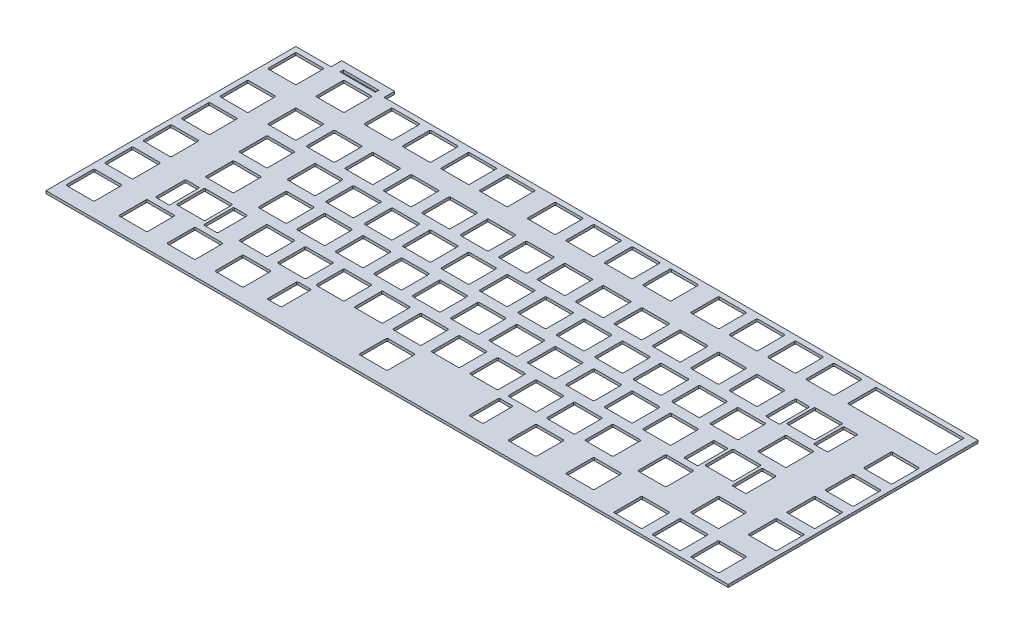
SolidWorks part; units mm, degrees
ref_plane "Front" through (0, 0, 0) normal (0, 0, 1) x (1, 0, 0)
ref_plane "Top" through (0, 0, 0) normal (0, 1, 0) x (1, 0, 0)
ref_plane "Right" through (0, 0, 0) normal (1, 0, 0) x (0, 0, -1)
sketch "Sketch5" plane through (0, 0, 0) normal (0, 1, 0) x (1, 0, 0)
  line L0 (3.4571, -2.8857) -> (18.3143, -2.8857)
  line L1 (3.4571, -18.8857) -> (18.3143, -18.8857)
  line L2 (2.8857, -3.4571) -> (2.8857, -18.3143)
  line L3 (18.8857, -3.4571) -> (18.8857, -18.3143)
  line L4 (30.6714, -2.8857) -> (45.5286, -2.8857)
  line L5 (30.6714, -18.8857) -> (45.5286, -18.8857)
  line L6 (30.1, -3.4571) -> (30.1, -18.3143)
  line L7 (46.1, -3.4571) -> (46.1, -18.3143)
  line L8 (57.8857, -2.8857) -> (72.7429, -2.8857)
  line L9 (57.8857, -18.8857) -> (72.7429, -18.8857)
  line L10 (57.3143, -3.4571) -> (57.3143, -18.3143)
  line L11 (73.3143, -3.4571) -> (73.3143, -18.3143)
  line L12 (79.6571, -2.8857) -> (94.5143, -2.8857)
  line L13 (79.6571, -18.8857) -> (94.5143, -18.8857)
  line L14 (79.0857, -3.4571) -> (79.0857, -18.3143)
  line L15 (95.0857, -3.4571) -> (95.0857, -18.3143)
  line L16 (101.4286, -2.8857) -> (116.2857, -2.8857)
  line L17 (101.4286, -18.8857) -> (116.2857, -18.8857)
  line L18 (100.8571, -3.4571) -> (100.8571, -18.3143)
  line L19 (116.8571, -3.4571) -> (116.8571, -18.3143)
  line L20 (123.2, -2.8857) -> (138.0571, -2.8857)
  line L21 (123.2, -18.8857) -> (138.0571, -18.8857)
  line L22 (122.6286, -3.4571) -> (122.6286, -18.3143)
  line L23 (138.6286, -3.4571) -> (138.6286, -18.3143)
  line L24 (150.4143, -2.8857) -> (165.2714, -2.8857)
  line L25 (150.4143, -18.8857) -> (165.2714, -18.8857)
  line L26 (149.8429, -3.4571) -> (149.8429, -18.3143)
  line L27 (165.8429, -3.4571) -> (165.8429, -18.3143)
  line L28 (172.1857, -2.8857) -> (187.0429, -2.8857)
  line L29 (172.1857, -18.8857) -> (187.0429, -18.8857)
  line L30 (171.6143, -3.4571) -> (171.6143, -18.3143)
  line L31 (187.6143, -3.4571) -> (187.6143, -18.3143)
  line L32 (193.9571, -2.8857) -> (208.8143, -2.8857)
  line L33 (193.9571, -18.8857) -> (208.8143, -18.8857)
  line L34 (193.3857, -3.4571) -> (193.3857, -18.3143)
  line L35 (209.3857, -3.4571) -> (209.3857, -18.3143)
  line L36 (215.7286, -2.8857) -> (230.5857, -2.8857)
  line L37 (215.7286, -18.8857) -> (230.5857, -18.8857)
  line L38 (215.1571, -3.4571) -> (215.1571, -18.3143)
  line L39 (231.1571, -3.4571) -> (231.1571, -18.3143)
  line L40 (242.9429, -2.8857) -> (257.8, -2.8857)
  line L41 (242.9429, -18.8857) -> (257.8, -18.8857)
  line L42 (242.3714, -3.4571) -> (242.3714, -18.3143)
  line L43 (258.3714, -3.4571) -> (258.3714, -18.3143)
  line L44 (264.7143, -2.8857) -> (279.5714, -2.8857)
  line L45 (264.7143, -18.8857) -> (279.5714, -18.8857)
  line L46 (264.1429, -3.4571) -> (264.1429, -18.3143)
  line L47 (280.1429, -3.4571) -> (280.1429, -18.3143)
  line L48 (286.4857, -2.8857) -> (301.3429, -2.8857)
  line L49 (286.4857, -18.8857) -> (301.3429, -18.8857)
  line L50 (285.9143, -3.4571) -> (285.9143, -18.3143)
  line L51 (301.9143, -3.4571) -> (301.9143, -18.3143)
  line L52 (308.2571, -2.8857) -> (323.1143, -2.8857)
  line L53 (308.2571, -18.8857) -> (323.1143, -18.8857)
  line L54 (307.6857, -3.4571) -> (307.6857, -18.3143)
  line L55 (323.6857, -3.4571) -> (323.6857, -18.3143)
  line L57 (331.4831, -2.8857) -> (381.4831, -2.8857)
  line L58 (331.4831, -2.8857) -> (331.4831, -18.8857)
  line L59 (331.4831, -18.8857) -> (381.4831, -18.8857)
  line L60 (381.4831, -2.8857) -> (381.4831, -18.8857)
  line L68 (3.4571, -30.1) -> (18.3143, -30.1)
  line L69 (3.4571, -46.1) -> (18.3143, -46.1)
  line L70 (2.8857, -30.6714) -> (2.8857, -45.5286)
  line L71 (18.8857, -30.6714) -> (18.8857, -45.5286)
  line L72 (30.6714, -30.1) -> (45.5286, -30.1)
  line L73 (30.6714, -46.1) -> (45.5286, -46.1)
  line L74 (30.1, -30.6714) -> (30.1, -45.5286)
  line L75 (46.1, -30.6714) -> (46.1, -45.5286)
  line L76 (52.4429, -30.1) -> (67.3, -30.1)
  line L77 (52.4429, -46.1) -> (67.3, -46.1)
  line L78 (51.8714, -30.6714) -> (51.8714, -45.5286)
  line L79 (67.8714, -30.6714) -> (67.8714, -45.5286)
  line L80 (74.2143, -30.1) -> (89.0714, -30.1)
  line L81 (74.2143, -46.1) -> (89.0714, -46.1)
  line L82 (73.6429, -30.6714) -> (73.6429, -45.5286)
  line L83 (89.6429, -30.6714) -> (89.6429, -45.5286)
  line L84 (95.9857, -30.1) -> (110.8429, -30.1)
  line L85 (95.9857, -46.1) -> (110.8429, -46.1)
  line L86 (95.4143, -30.6714) -> (95.4143, -45.5286)
  line L87 (111.4143, -30.6714) -> (111.4143, -45.5286)
  line L88 (117.7571, -30.1) -> (132.6143, -30.1)
  line L89 (117.7571, -46.1) -> (132.6143, -46.1)
  line L90 (117.1857, -30.6714) -> (117.1857, -45.5286)
  line L91 (133.1857, -30.6714) -> (133.1857, -45.5286)
  line L92 (139.5286, -30.1) -> (154.3857, -30.1)
  line L93 (139.5286, -46.1) -> (154.3857, -46.1)
  line L94 (138.9571, -30.6714) -> (138.9571, -45.5286)
  line L95 (154.9571, -30.6714) -> (154.9571, -45.5286)
  line L96 (161.3, -30.1) -> (176.1571, -30.1)
  line L97 (161.3, -46.1) -> (176.1571, -46.1)
  line L98 (160.7286, -30.6714) -> (160.7286, -45.5286)
  line L99 (176.7286, -30.6714) -> (176.7286, -45.5286)
  line L100 (183.0714, -30.1) -> (197.9286, -30.1)
  line L101 (183.0714, -46.1) -> (197.9286, -46.1)
  line L102 (182.5, -30.6714) -> (182.5, -45.5286)
  line L103 (198.5, -30.6714) -> (198.5, -45.5286)
  line L104 (204.8429, -30.1) -> (219.7, -30.1)
  line L105 (204.8429, -46.1) -> (219.7, -46.1)
  line L106 (204.2714, -30.6714) -> (204.2714, -45.5286)
  line L107 (220.2714, -30.6714) -> (220.2714, -45.5286)
  line L108 (226.6143, -30.1) -> (241.4714, -30.1)
  line L109 (226.6143, -46.1) -> (241.4714, -46.1)
  line L110 (226.0429, -30.6714) -> (226.0429, -45.5286)
  line L111 (242.0429, -30.6714) -> (242.0429, -45.5286)
  line L112 (248.3857, -30.1) -> (263.2429, -30.1)
  line L113 (248.3857, -46.1) -> (263.2429, -46.1)
  line L114 (247.8143, -30.6714) -> (247.8143, -45.5286)
  line L115 (263.8143, -30.6714) -> (263.8143, -45.5286)
  line L116 (270.1571, -30.1) -> (285.0143, -30.1)
  line L117 (270.1571, -46.1) -> (285.0143, -46.1)
  line L118 (269.5857, -30.6714) -> (269.5857, -45.5286)
  line L119 (285.5857, -30.6714) -> (285.5857, -45.5286)
  line L120 (291.9286, -30.1) -> (306.7857, -30.1)
  line L121 (291.9286, -46.1) -> (306.7857, -46.1)
  line L122 (291.3571, -30.6714) -> (291.3571, -45.5286)
  line L123 (307.3571, -30.6714) -> (307.3571, -45.5286)
  line L124 (324.5857, -30.1) -> (339.4429, -30.1)
  line L125 (324.5857, -46.1) -> (339.4429, -46.1)
  line L126 (324.0143, -30.6714) -> (324.0143, -45.5286)
  line L127 (340.0143, -30.6714) -> (340.0143, -45.5286)
  line L128 (314.9423, -31.2429) -> (321.7994, -31.2429)
  line L129 (314.9423, -48.3857) -> (321.7994, -48.3857)
  line L130 (314.3709, -31.8143) -> (314.3709, -47.8143)
  line L131 (322.3709, -31.8143) -> (322.3709, -47.8143)
  line L132 (342.2291, -31.2429) -> (349.0863, -31.2429)
  line L133 (342.2291, -48.3857) -> (349.0863, -48.3857)
  line L134 (341.6577, -31.8143) -> (341.6577, -47.8143)
  line L135 (349.6577, -31.8143) -> (349.6577, -47.8143)
  line L136 (368.1286, -30.1) -> (382.9857, -30.1)
  line L137 (368.1286, -46.1) -> (382.9857, -46.1)
  line L138 (367.5571, -30.6714) -> (367.5571, -45.5286)
  line L139 (383.5571, -30.6714) -> (383.5571, -45.5286)
  line L140 (3.4571, -51.8714) -> (18.3143, -51.8714)
  line L141 (3.4571, -67.8714) -> (18.3143, -67.8714)
  line L142 (2.8857, -52.4429) -> (2.8857, -67.3)
  line L143 (18.8857, -52.4429) -> (18.8857, -67.3)
  line L144 (36.1143, -51.8714) -> (50.9714, -51.8714)
  line L145 (36.1143, -67.8714) -> (50.9714, -67.8714)
  line L146 (35.5429, -52.4429) -> (35.5429, -67.3)
  line L147 (51.5429, -52.4429) -> (51.5429, -67.3)
  line L148 (63.3286, -51.8714) -> (78.1857, -51.8714)
  line L149 (63.3286, -67.8714) -> (78.1857, -67.8714)
  line L150 (62.7571, -52.4429) -> (62.7571, -67.3)
  line L151 (78.7571, -52.4429) -> (78.7571, -67.3)
  line L152 (85.1, -51.8714) -> (99.9571, -51.8714)
  line L153 (85.1, -67.8714) -> (99.9571, -67.8714)
  line L154 (84.5286, -52.4429) -> (84.5286, -67.3)
  line L155 (100.5286, -52.4429) -> (100.5286, -67.3)
  line L156 (106.8714, -51.8714) -> (121.7286, -51.8714)
  line L157 (106.8714, -67.8714) -> (121.7286, -67.8714)
  line L158 (106.3, -52.4429) -> (106.3, -67.3)
  line L159 (122.3, -52.4429) -> (122.3, -67.3)
  line L160 (128.6429, -51.8714) -> (143.5, -51.8714)
  line L161 (128.6429, -67.8714) -> (143.5, -67.8714)
  line L162 (128.0714, -52.4429) -> (128.0714, -67.3)
  line L163 (144.0714, -52.4429) -> (144.0714, -67.3)
  line L164 (150.4143, -51.8714) -> (165.2714, -51.8714)
  line L165 (150.4143, -67.8714) -> (165.2714, -67.8714)
  line L166 (149.8429, -52.4429) -> (149.8429, -67.3)
  line L167 (165.8429, -52.4429) -> (165.8429, -67.3)
  line L168 (172.1857, -51.8714) -> (187.0429, -51.8714)
  line L169 (172.1857, -67.8714) -> (187.0429, -67.8714)
  line L170 (171.6143, -52.4429) -> (171.6143, -67.3)
  line L171 (187.6143, -52.4429) -> (187.6143, -67.3)
  line L172 (193.9571, -51.8714) -> (208.8143, -51.8714)
  line L173 (193.9571, -67.8714) -> (208.8143, -67.8714)
  line L174 (193.3857, -52.4429) -> (193.3857, -67.3)
  line L175 (209.3857, -52.4429) -> (209.3857, -67.3)
  line L176 (215.7286, -51.8714) -> (230.5857, -51.8714)
  line L177 (215.7286, -67.8714) -> (230.5857, -67.8714)
  line L178 (215.1571, -52.4429) -> (215.1571, -67.3)
  line L179 (231.1571, -52.4429) -> (231.1571, -67.3)
  line L180 (237.5, -51.8714) -> (252.3571, -51.8714)
  line L181 (237.5, -67.8714) -> (252.3571, -67.8714)
  line L182 (236.9286, -52.4429) -> (236.9286, -67.3)
  line L183 (252.9286, -52.4429) -> (252.9286, -67.3)
  line L184 (259.2714, -51.8714) -> (274.1286, -51.8714)
  line L185 (259.2714, -67.8714) -> (274.1286, -67.8714)
  line L186 (258.7, -52.4429) -> (258.7, -67.3)
  line L187 (274.7, -52.4429) -> (274.7, -67.3)
  line L188 (281.0429, -51.8714) -> (295.9, -51.8714)
  line L189 (281.0429, -67.8714) -> (295.9, -67.8714)
  line L190 (280.4714, -52.4429) -> (280.4714, -67.3)
  line L191 (296.4714, -52.4429) -> (296.4714, -67.3)
  line L192 (302.8143, -51.8714) -> (317.6714, -51.8714)
  line L193 (302.8143, -67.8714) -> (317.6714, -67.8714)
  line L194 (302.2429, -52.4429) -> (302.2429, -67.3)
  line L195 (318.2429, -52.4429) -> (318.2429, -67.3)
  line L196 (330.0286, -51.8714) -> (344.8857, -51.8714)
  line L197 (330.0286, -67.8714) -> (344.8857, -67.8714)
  line L198 (329.4571, -52.4429) -> (329.4571, -67.3)
  line L199 (345.4571, -52.4429) -> (345.4571, -67.3)
  line L200 (368.1286, -51.8714) -> (382.9857, -51.8714)
  line L201 (368.1286, -67.8714) -> (382.9857, -67.8714)
  line L202 (367.5571, -52.4429) -> (367.5571, -67.3)
  line L203 (383.5571, -52.4429) -> (383.5571, -67.3)
  line L204 (3.4571, -73.6429) -> (18.3143, -73.6429)
  line L205 (3.4571, -89.6429) -> (18.3143, -89.6429)
  line L206 (2.8857, -74.2143) -> (2.8857, -89.0714)
  line L207 (18.8857, -74.2143) -> (18.8857, -89.0714)
  line L208 (38.8357, -73.6429) -> (53.6929, -73.6429)
  line L209 (38.8357, -89.6429) -> (53.6929, -89.6429)
  line L210 (38.2643, -74.2143) -> (38.2643, -89.0714)
  line L211 (54.2643, -74.2143) -> (54.2643, -89.0714)
  line L212 (68.7714, -73.6429) -> (83.6286, -73.6429)
  line L213 (68.7714, -89.6429) -> (83.6286, -89.6429)
  line L214 (68.2, -74.2143) -> (68.2, -89.0714)
  line L215 (84.2, -74.2143) -> (84.2, -89.0714)
  line L216 (90.5429, -73.6429) -> (105.4, -73.6429)
  line L217 (90.5429, -89.6429) -> (105.4, -89.6429)
  line L218 (89.9714, -74.2143) -> (89.9714, -89.0714)
  line L219 (105.9714, -74.2143) -> (105.9714, -89.0714)
  line L220 (112.3143, -73.6429) -> (127.1714, -73.6429)
  line L221 (112.3143, -89.6429) -> (127.1714, -89.6429)
  line L222 (111.7429, -74.2143) -> (111.7429, -89.0714)
  line L223 (127.7429, -74.2143) -> (127.7429, -89.0714)
  line L224 (134.0857, -73.6429) -> (148.9429, -73.6429)
  line L225 (134.0857, -89.6429) -> (148.9429, -89.6429)
  line L226 (133.5143, -74.2143) -> (133.5143, -89.0714)
  line L227 (149.5143, -74.2143) -> (149.5143, -89.0714)
  line L228 (155.8571, -73.6429) -> (170.7143, -73.6429)
  line L229 (155.8571, -89.6429) -> (170.7143, -89.6429)
  line L230 (155.2857, -74.2143) -> (155.2857, -89.0714)
  line L231 (171.2857, -74.2143) -> (171.2857, -89.0714)
  line L232 (177.6286, -73.6429) -> (192.4857, -73.6429)
  line L233 (177.6286, -89.6429) -> (192.4857, -89.6429)
  line L234 (177.0571, -74.2143) -> (177.0571, -89.0714)
  line L235 (193.0571, -74.2143) -> (193.0571, -89.0714)
  line L236 (199.4, -73.6429) -> (214.2571, -73.6429)
  line L237 (199.4, -89.6429) -> (214.2571, -89.6429)
  line L238 (198.8286, -74.2143) -> (198.8286, -89.0714)
  line L239 (214.8286, -74.2143) -> (214.8286, -89.0714)
  line L240 (221.1714, -73.6429) -> (236.0286, -73.6429)
  line L241 (221.1714, -89.6429) -> (236.0286, -89.6429)
  line L242 (220.6, -74.2143) -> (220.6, -89.0714)
  line L243 (236.6, -74.2143) -> (236.6, -89.0714)
  line L244 (242.9429, -73.6429) -> (257.8, -73.6429)
  line L245 (242.9429, -89.6429) -> (257.8, -89.6429)
  line L246 (242.3714, -74.2143) -> (242.3714, -89.0714)
  line L247 (258.3714, -74.2143) -> (258.3714, -89.0714)
  line L248 (264.7143, -73.6429) -> (279.5714, -73.6429)
  line L249 (264.7143, -89.6429) -> (279.5714, -89.6429)
  line L250 (264.1429, -74.2143) -> (264.1429, -89.0714)
  line L251 (280.1429, -74.2143) -> (280.1429, -89.0714)
  line L252 (286.4857, -73.6429) -> (301.3429, -73.6429)
  line L253 (286.4857, -89.6429) -> (301.3429, -89.6429)
  line L254 (285.9143, -74.2143) -> (285.9143, -89.0714)
  line L255 (301.9143, -74.2143) -> (301.9143, -89.0714)
  line L256 (321.8643, -73.6429) -> (336.7214, -73.6429)
  line L257 (321.8643, -89.6429) -> (336.7214, -89.6429)
  line L258 (321.2929, -74.2143) -> (321.2929, -89.0714)
  line L259 (337.2929, -74.2143) -> (337.2929, -89.0714)
  line L260 (312.2209, -74.7857) -> (319.078, -74.7857)
  line L261 (312.2209, -91.9286) -> (319.078, -91.9286)
  line L262 (311.6494, -75.3571) -> (311.6494, -91.3571)
  line L263 (319.6494, -75.3571) -> (319.6494, -91.3571)
  line L264 (339.5077, -74.7857) -> (346.3649, -74.7857)
  line L265 (339.5077, -91.9286) -> (346.3649, -91.9286)
  line L266 (338.9363, -75.3571) -> (338.9363, -91.3571)
  line L267 (346.9363, -75.3571) -> (346.9363, -91.3571)
  line L268 (368.1286, -73.6429) -> (382.9857, -73.6429)
  line L269 (368.1286, -89.6429) -> (382.9857, -89.6429)
  line L270 (367.5571, -74.2143) -> (367.5571, -89.0714)
  line L271 (383.5571, -74.2143) -> (383.5571, -89.0714)
  line L272 (3.4571, -95.4143) -> (18.3143, -95.4143)
  line L273 (3.4571, -111.4143) -> (18.3143, -111.4143)
  line L274 (2.8857, -95.9857) -> (2.8857, -110.8429)
  line L275 (18.8857, -95.9857) -> (18.8857, -110.8429)
  line L276 (44.2786, -95.4143) -> (59.1357, -95.4143)
  line L277 (44.2786, -111.4143) -> (59.1357, -111.4143)
  line L278 (43.7071, -95.9857) -> (43.7071, -110.8429)
  line L279 (59.7071, -95.9857) -> (59.7071, -110.8429)
  line L280 (34.6351, -96.5571) -> (41.4923, -96.5571)
  line L281 (34.6351, -113.7) -> (41.4923, -113.7)
  line L282 (34.0637, -97.1286) -> (34.0637, -113.1286)
  line L283 (42.0637, -97.1286) -> (42.0637, -113.1286)
  line L284 (61.922, -96.5571) -> (68.7791, -96.5571)
  line L285 (61.922, -113.7) -> (68.7791, -113.7)
  line L286 (61.3506, -97.1286) -> (61.3506, -113.1286)
  line L287 (69.3506, -97.1286) -> (69.3506, -113.1286)
  line L288 (79.6571, -95.4143) -> (94.5143, -95.4143)
  line L289 (79.6571, -111.4143) -> (94.5143, -111.4143)
  line L290 (79.0857, -95.9857) -> (79.0857, -110.8429)
  line L291 (95.0857, -95.9857) -> (95.0857, -110.8429)
  line L292 (101.4286, -95.4143) -> (116.2857, -95.4143)
  line L293 (101.4286, -111.4143) -> (116.2857, -111.4143)
  line L294 (100.8571, -95.9857) -> (100.8571, -110.8429)
  line L295 (116.8571, -95.9857) -> (116.8571, -110.8429)
  line L296 (123.2, -95.4143) -> (138.0571, -95.4143)
  line L297 (123.2, -111.4143) -> (138.0571, -111.4143)
  line L298 (122.6286, -95.9857) -> (122.6286, -110.8429)
  line L299 (138.6286, -95.9857) -> (138.6286, -110.8429)
  line L300 (144.9714, -95.4143) -> (159.8286, -95.4143)
  line L301 (144.9714, -111.4143) -> (159.8286, -111.4143)
  line L302 (144.4, -95.9857) -> (144.4, -110.8429)
  line L303 (160.4, -95.9857) -> (160.4, -110.8429)
  line L304 (166.7429, -95.4143) -> (181.6, -95.4143)
  line L305 (166.7429, -111.4143) -> (181.6, -111.4143)
  line L306 (166.1714, -95.9857) -> (166.1714, -110.8429)
  line L307 (182.1714, -95.9857) -> (182.1714, -110.8429)
  line L308 (188.5143, -95.4143) -> (203.3714, -95.4143)
  line L309 (188.5143, -111.4143) -> (203.3714, -111.4143)
  line L310 (187.9429, -95.9857) -> (187.9429, -110.8429)
  line L311 (203.9429, -95.9857) -> (203.9429, -110.8429)
  line L312 (210.2857, -95.4143) -> (225.1429, -95.4143)
  line L313 (210.2857, -111.4143) -> (225.1429, -111.4143)
  line L314 (209.7143, -95.9857) -> (209.7143, -110.8429)
  line L315 (225.7143, -95.9857) -> (225.7143, -110.8429)
  line L316 (232.0571, -95.4143) -> (246.9143, -95.4143)
  line L317 (232.0571, -111.4143) -> (246.9143, -111.4143)
  line L318 (231.4857, -95.9857) -> (231.4857, -110.8429)
  line L319 (247.4857, -95.9857) -> (247.4857, -110.8429)
  line L320 (253.8286, -95.4143) -> (268.6857, -95.4143)
  line L321 (253.8286, -111.4143) -> (268.6857, -111.4143)
  line L322 (253.2571, -95.9857) -> (253.2571, -110.8429)
  line L323 (269.2571, -95.9857) -> (269.2571, -110.8429)
  line L324 (275.6, -95.4143) -> (290.4571, -95.4143)
  line L325 (275.6, -111.4143) -> (290.4571, -111.4143)
  line L326 (275.0286, -95.9857) -> (275.0286, -110.8429)
  line L327 (291.0286, -95.9857) -> (291.0286, -110.8429)
  line L328 (305.5357, -95.4143) -> (320.3929, -95.4143)
  line L329 (305.5357, -111.4143) -> (320.3929, -111.4143)
  line L330 (304.9643, -95.9857) -> (304.9643, -110.8429)
  line L331 (320.9643, -95.9857) -> (320.9643, -110.8429)
  line L332 (368.1286, -95.4143) -> (382.9857, -95.4143)
  line L333 (368.1286, -111.4143) -> (382.9857, -111.4143)
  line L334 (367.5571, -95.9857) -> (367.5571, -110.8429)
  line L335 (383.5571, -95.9857) -> (383.5571, -110.8429)
  line L336 (340.9143, -100.8571) -> (355.7714, -100.8571)
  line L337 (340.9143, -116.8571) -> (355.7714, -116.8571)
  line L338 (340.3429, -101.4286) -> (340.3429, -116.2857)
  line L339 (356.3429, -101.4286) -> (356.3429, -116.2857)
  line L340 (3.4571, -117.1857) -> (18.3143, -117.1857)
  line L341 (3.4571, -133.1857) -> (18.3143, -133.1857)
  line L342 (2.8857, -117.7571) -> (2.8857, -132.6143)
  line L343 (18.8857, -117.7571) -> (18.8857, -132.6143)
  line L344 (33.3929, -117.1857) -> (48.25, -117.1857)
  line L345 (33.3929, -133.1857) -> (48.25, -133.1857)
  line L346 (32.8214, -117.7571) -> (32.8214, -132.6143)
  line L347 (48.8214, -117.7571) -> (48.8214, -132.6143)
  line L348 (60.6071, -117.1857) -> (75.4643, -117.1857)
  line L349 (60.6071, -133.1857) -> (75.4643, -133.1857)
  line L350 (60.0357, -117.7571) -> (60.0357, -132.6143)
  line L351 (76.0357, -117.7571) -> (76.0357, -132.6143)
  line L352 (87.8214, -117.1857) -> (102.6786, -117.1857)
  line L353 (87.8214, -133.1857) -> (102.6786, -133.1857)
  line L354 (87.25, -117.7571) -> (87.25, -132.6143)
  line L355 (103.25, -117.7571) -> (103.25, -132.6143)
  line L356 (169.4643, -117.1857) -> (184.3214, -117.1857)
  line L357 (169.4643, -133.1857) -> (184.3214, -133.1857)
  line L358 (168.8929, -117.7571) -> (168.8929, -132.6143)
  line L359 (184.8929, -117.7571) -> (184.8929, -132.6143)
  line L360 (237.4643, -132.0429) -> (230.6071, -132.0429)
  line L361 (237.4643, -114.9) -> (230.6071, -114.9)
  line L362 (238.0357, -131.4714) -> (238.0357, -115.4714)
  line L363 (230.0357, -131.4714) -> (230.0357, -115.4714)
  line L364 (123.1786, -132.0429) -> (116.3214, -132.0429)
  line L365 (123.1786, -114.9) -> (116.3214, -114.9)
  line L366 (123.75, -131.4714) -> (123.75, -115.4714)
  line L367 (115.75, -131.4714) -> (115.75, -115.4714)
  line L368 (253.8286, -117.1857) -> (268.6857, -117.1857)
  line L369 (253.8286, -133.1857) -> (268.6857, -133.1857)
  line L370 (253.2571, -117.7571) -> (253.2571, -132.6143)
  line L371 (269.2571, -117.7571) -> (269.2571, -132.6143)
  line L372 (286.4857, -117.1857) -> (301.3429, -117.1857)
  line L373 (286.4857, -133.1857) -> (301.3429, -133.1857)
  line L374 (285.9143, -117.7571) -> (285.9143, -132.6143)
  line L375 (301.9143, -117.7571) -> (301.9143, -132.6143)
  line L376 (319.1429, -122.6286) -> (334, -122.6286)
  line L377 (319.1429, -138.6286) -> (334, -138.6286)
  line L378 (318.5714, -123.2) -> (318.5714, -138.0571)
  line L379 (334.5714, -123.2) -> (334.5714, -138.0571)
  line L380 (340.9143, -122.6286) -> (355.7714, -122.6286)
  line L381 (340.9143, -138.6286) -> (355.7714, -138.6286)
  line L382 (340.3429, -123.2) -> (340.3429, -138.0571)
  line L383 (356.3429, -123.2) -> (356.3429, -138.0571)
  line L384 (362.6857, -122.6286) -> (377.5429, -122.6286)
  line L385 (362.6857, -138.6286) -> (377.5429, -138.6286)
  line L386 (362.1143, -123.2) -> (362.1143, -138.0571)
  line L387 (378.1143, -123.2) -> (378.1143, -138.0571)
  line L388 (0, -141.5143) -> (386.4429, -141.5143)
  line L390 (0, -141.5143) -> (0, 0)
  line L391 (386.4429, -141.5143) -> (386.4429, 0)
  line L411 (0, 0) -> (20, 0)
  line L414 (20, 0) -> (20, 6)
  line L415 (386.4429, -70.7571) -> (-204.0743, -70.7571) construction
  line L422 (20, 6) -> (50, 6)
  line L433 (50, 6) -> (50, 0)
  line L435 (45, 0) -> (45, 2)
  line L436 (45, 2) -> (25, 2)
  line L437 (25, 2) -> (25, 0)
  line L439 (25, 0) -> (45, 0)
  line L440 (50, 0) -> (386.4429, 0)
  arc A0 (3.4571, -2.8857) -> (2.8857, -3.4571) centre (3.4571, -3.4571) ccw
  arc A1 (18.8857, -3.4571) -> (18.3143, -2.8857) centre (18.3143, -3.4571) ccw
  arc A2 (2.8857, -18.3143) -> (3.4571, -18.8857) centre (3.4571, -18.3143) ccw
  arc A3 (18.3143, -18.8857) -> (18.8857, -18.3143) centre (18.3143, -18.3143) ccw
  arc A4 (30.6714, -2.8857) -> (30.1, -3.4571) centre (30.6714, -3.4571) ccw
  arc A5 (46.1, -3.4571) -> (45.5286, -2.8857) centre (45.5286, -3.4571) ccw
  arc A6 (30.1, -18.3143) -> (30.6714, -18.8857) centre (30.6714, -18.3143) ccw
  arc A7 (45.5286, -18.8857) -> (46.1, -18.3143) centre (45.5286, -18.3143) ccw
  arc A8 (57.8857, -2.8857) -> (57.3143, -3.4571) centre (57.8857, -3.4571) ccw
  arc A9 (73.3143, -3.4571) -> (72.7429, -2.8857) centre (72.7429, -3.4571) ccw
  arc A10 (57.3143, -18.3143) -> (57.8857, -18.8857) centre (57.8857, -18.3143) ccw
  arc A11 (72.7429, -18.8857) -> (73.3143, -18.3143) centre (72.7429, -18.3143) ccw
  arc A12 (79.6571, -2.8857) -> (79.0857, -3.4571) centre (79.6571, -3.4571) ccw
  arc A13 (95.0857, -3.4571) -> (94.5143, -2.8857) centre (94.5143, -3.4571) ccw
  arc A14 (79.0857, -18.3143) -> (79.6571, -18.8857) centre (79.6571, -18.3143) ccw
  arc A15 (94.5143, -18.8857) -> (95.0857, -18.3143) centre (94.5143, -18.3143) ccw
  arc A16 (101.4286, -2.8857) -> (100.8571, -3.4571) centre (101.4286, -3.4571) ccw
  arc A17 (116.8571, -3.4571) -> (116.2857, -2.8857) centre (116.2857, -3.4571) ccw
  arc A18 (100.8571, -18.3143) -> (101.4286, -18.8857) centre (101.4286, -18.3143) ccw
  arc A19 (116.2857, -18.8857) -> (116.8571, -18.3143) centre (116.2857, -18.3143) ccw
  arc A20 (123.2, -2.8857) -> (122.6286, -3.4571) centre (123.2, -3.4571) ccw
  arc A21 (138.6286, -3.4571) -> (138.0571, -2.8857) centre (138.0571, -3.4571) ccw
  arc A22 (122.6286, -18.3143) -> (123.2, -18.8857) centre (123.2, -18.3143) ccw
  arc A23 (138.0571, -18.8857) -> (138.6286, -18.3143) centre (138.0571, -18.3143) ccw
  arc A24 (150.4143, -2.8857) -> (149.8429, -3.4571) centre (150.4143, -3.4571) ccw
  arc A25 (165.8429, -3.4571) -> (165.2714, -2.8857) centre (165.2714, -3.4571) ccw
  arc A26 (149.8429, -18.3143) -> (150.4143, -18.8857) centre (150.4143, -18.3143) ccw
  arc A27 (165.2714, -18.8857) -> (165.8429, -18.3143) centre (165.2714, -18.3143) ccw
  arc A28 (172.1857, -2.8857) -> (171.6143, -3.4571) centre (172.1857, -3.4571) ccw
  arc A29 (187.6143, -3.4571) -> (187.0429, -2.8857) centre (187.0429, -3.4571) ccw
  arc A30 (171.6143, -18.3143) -> (172.1857, -18.8857) centre (172.1857, -18.3143) ccw
  arc A31 (187.0429, -18.8857) -> (187.6143, -18.3143) centre (187.0429, -18.3143) ccw
  arc A32 (193.9571, -2.8857) -> (193.3857, -3.4571) centre (193.9571, -3.4571) ccw
  arc A33 (209.3857, -3.4571) -> (208.8143, -2.8857) centre (208.8143, -3.4571) ccw
  arc A34 (193.3857, -18.3143) -> (193.9571, -18.8857) centre (193.9571, -18.3143) ccw
  arc A35 (208.8143, -18.8857) -> (209.3857, -18.3143) centre (208.8143, -18.3143) ccw
  arc A36 (215.7286, -2.8857) -> (215.1571, -3.4571) centre (215.7286, -3.4571) ccw
  arc A37 (231.1571, -3.4571) -> (230.5857, -2.8857) centre (230.5857, -3.4571) ccw
  arc A38 (215.1571, -18.3143) -> (215.7286, -18.8857) centre (215.7286, -18.3143) ccw
  arc A39 (230.5857, -18.8857) -> (231.1571, -18.3143) centre (230.5857, -18.3143) ccw
  arc A40 (242.9429, -2.8857) -> (242.3714, -3.4571) centre (242.9429, -3.4571) ccw
  arc A41 (258.3714, -3.4571) -> (257.8, -2.8857) centre (257.8, -3.4571) ccw
  arc A42 (242.3714, -18.3143) -> (242.9429, -18.8857) centre (242.9429, -18.3143) ccw
  arc A43 (257.8, -18.8857) -> (258.3714, -18.3143) centre (257.8, -18.3143) ccw
  arc A44 (264.7143, -2.8857) -> (264.1429, -3.4571) centre (264.7143, -3.4571) ccw
  arc A45 (280.1429, -3.4571) -> (279.5714, -2.8857) centre (279.5714, -3.4571) ccw
  arc A46 (264.1429, -18.3143) -> (264.7143, -18.8857) centre (264.7143, -18.3143) ccw
  arc A47 (279.5714, -18.8857) -> (280.1429, -18.3143) centre (279.5714, -18.3143) ccw
  arc A48 (286.4857, -2.8857) -> (285.9143, -3.4571) centre (286.4857, -3.4571) ccw
  arc A49 (301.9143, -3.4571) -> (301.3429, -2.8857) centre (301.3429, -3.4571) ccw
  arc A50 (285.9143, -18.3143) -> (286.4857, -18.8857) centre (286.4857, -18.3143) ccw
  arc A51 (301.3429, -18.8857) -> (301.9143, -18.3143) centre (301.3429, -18.3143) ccw
  arc A52 (308.2571, -2.8857) -> (307.6857, -3.4571) centre (308.2571, -3.4571) ccw
  arc A53 (323.6857, -3.4571) -> (323.1143, -2.8857) centre (323.1143, -3.4571) ccw
  arc A54 (307.6857, -18.3143) -> (308.2571, -18.8857) centre (308.2571, -18.3143) ccw
  arc A55 (323.1143, -18.8857) -> (323.6857, -18.3143) centre (323.1143, -18.3143) ccw
  arc A68 (3.4571, -30.1) -> (2.8857, -30.6714) centre (3.4571, -30.6714) ccw
  arc A69 (18.8857, -30.6714) -> (18.3143, -30.1) centre (18.3143, -30.6714) ccw
  arc A70 (2.8857, -45.5286) -> (3.4571, -46.1) centre (3.4571, -45.5286) ccw
  arc A71 (18.3143, -46.1) -> (18.8857, -45.5286) centre (18.3143, -45.5286) ccw
  arc A72 (30.6714, -30.1) -> (30.1, -30.6714) centre (30.6714, -30.6714) ccw
  arc A73 (46.1, -30.6714) -> (45.5286, -30.1) centre (45.5286, -30.6714) ccw
  arc A74 (30.1, -45.5286) -> (30.6714, -46.1) centre (30.6714, -45.5286) ccw
  arc A75 (45.5286, -46.1) -> (46.1, -45.5286) centre (45.5286, -45.5286) ccw
  arc A76 (52.4429, -30.1) -> (51.8714, -30.6714) centre (52.4429, -30.6714) ccw
  arc A77 (67.8714, -30.6714) -> (67.3, -30.1) centre (67.3, -30.6714) ccw
  arc A78 (51.8714, -45.5286) -> (52.4429, -46.1) centre (52.4429, -45.5286) ccw
  arc A79 (67.3, -46.1) -> (67.8714, -45.5286) centre (67.3, -45.5286) ccw
  arc A80 (74.2143, -30.1) -> (73.6429, -30.6714) centre (74.2143, -30.6714) ccw
  arc A81 (89.6429, -30.6714) -> (89.0714, -30.1) centre (89.0714, -30.6714) ccw
  arc A82 (73.6429, -45.5286) -> (74.2143, -46.1) centre (74.2143, -45.5286) ccw
  arc A83 (89.0714, -46.1) -> (89.6429, -45.5286) centre (89.0714, -45.5286) ccw
  arc A84 (95.9857, -30.1) -> (95.4143, -30.6714) centre (95.9857, -30.6714) ccw
  arc A85 (111.4143, -30.6714) -> (110.8429, -30.1) centre (110.8429, -30.6714) ccw
  arc A86 (95.4143, -45.5286) -> (95.9857, -46.1) centre (95.9857, -45.5286) ccw
  arc A87 (110.8429, -46.1) -> (111.4143, -45.5286) centre (110.8429, -45.5286) ccw
  arc A88 (117.7571, -30.1) -> (117.1857, -30.6714) centre (117.7571, -30.6714) ccw
  arc A89 (133.1857, -30.6714) -> (132.6143, -30.1) centre (132.6143, -30.6714) ccw
  arc A90 (117.1857, -45.5286) -> (117.7571, -46.1) centre (117.7571, -45.5286) ccw
  arc A91 (132.6143, -46.1) -> (133.1857, -45.5286) centre (132.6143, -45.5286) ccw
  arc A92 (139.5286, -30.1) -> (138.9571, -30.6714) centre (139.5286, -30.6714) ccw
  arc A93 (154.9571, -30.6714) -> (154.3857, -30.1) centre (154.3857, -30.6714) ccw
  arc A94 (138.9571, -45.5286) -> (139.5286, -46.1) centre (139.5286, -45.5286) ccw
  arc A95 (154.3857, -46.1) -> (154.9571, -45.5286) centre (154.3857, -45.5286) ccw
  arc A96 (161.3, -30.1) -> (160.7286, -30.6714) centre (161.3, -30.6714) ccw
  arc A97 (176.7286, -30.6714) -> (176.1571, -30.1) centre (176.1571, -30.6714) ccw
  arc A98 (160.7286, -45.5286) -> (161.3, -46.1) centre (161.3, -45.5286) ccw
  arc A99 (176.1571, -46.1) -> (176.7286, -45.5286) centre (176.1571, -45.5286) ccw
  arc A100 (183.0714, -30.1) -> (182.5, -30.6714) centre (183.0714, -30.6714) ccw
  arc A101 (198.5, -30.6714) -> (197.9286, -30.1) centre (197.9286, -30.6714) ccw
  arc A102 (182.5, -45.5286) -> (183.0714, -46.1) centre (183.0714, -45.5286) ccw
  arc A103 (197.9286, -46.1) -> (198.5, -45.5286) centre (197.9286, -45.5286) ccw
  arc A104 (204.8429, -30.1) -> (204.2714, -30.6714) centre (204.8429, -30.6714) ccw
  arc A105 (220.2714, -30.6714) -> (219.7, -30.1) centre (219.7, -30.6714) ccw
  arc A106 (204.2714, -45.5286) -> (204.8429, -46.1) centre (204.8429, -45.5286) ccw
  arc A107 (219.7, -46.1) -> (220.2714, -45.5286) centre (219.7, -45.5286) ccw
  arc A108 (226.6143, -30.1) -> (226.0429, -30.6714) centre (226.6143, -30.6714) ccw
  arc A109 (242.0429, -30.6714) -> (241.4714, -30.1) centre (241.4714, -30.6714) ccw
  arc A110 (226.0429, -45.5286) -> (226.6143, -46.1) centre (226.6143, -45.5286) ccw
  arc A111 (241.4714, -46.1) -> (242.0429, -45.5286) centre (241.4714, -45.5286) ccw
  arc A112 (248.3857, -30.1) -> (247.8143, -30.6714) centre (248.3857, -30.6714) ccw
  arc A113 (263.8143, -30.6714) -> (263.2429, -30.1) centre (263.2429, -30.6714) ccw
  arc A114 (247.8143, -45.5286) -> (248.3857, -46.1) centre (248.3857, -45.5286) ccw
  arc A115 (263.2429, -46.1) -> (263.8143, -45.5286) centre (263.2429, -45.5286) ccw
  arc A116 (270.1571, -30.1) -> (269.5857, -30.6714) centre (270.1571, -30.6714) ccw
  arc A117 (285.5857, -30.6714) -> (285.0143, -30.1) centre (285.0143, -30.6714) ccw
  arc A118 (269.5857, -45.5286) -> (270.1571, -46.1) centre (270.1571, -45.5286) ccw
  arc A119 (285.0143, -46.1) -> (285.5857, -45.5286) centre (285.0143, -45.5286) ccw
  arc A120 (291.9286, -30.1) -> (291.3571, -30.6714) centre (291.9286, -30.6714) ccw
  arc A121 (307.3571, -30.6714) -> (306.7857, -30.1) centre (306.7857, -30.6714) ccw
  arc A122 (291.3571, -45.5286) -> (291.9286, -46.1) centre (291.9286, -45.5286) ccw
  arc A123 (306.7857, -46.1) -> (307.3571, -45.5286) centre (306.7857, -45.5286) ccw
  arc A124 (324.5857, -30.1) -> (324.0143, -30.6714) centre (324.5857, -30.6714) ccw
  arc A125 (340.0143, -30.6714) -> (339.4429, -30.1) centre (339.4429, -30.6714) ccw
  arc A126 (324.0143, -45.5286) -> (324.5857, -46.1) centre (324.5857, -45.5286) ccw
  arc A127 (339.4429, -46.1) -> (340.0143, -45.5286) centre (339.4429, -45.5286) ccw
  arc A128 (314.9423, -31.2429) -> (314.3709, -31.8143) centre (314.9423, -31.8143) ccw
  arc A129 (322.3709, -31.8143) -> (321.7994, -31.2429) centre (321.7994, -31.8143) ccw
  arc A130 (314.3709, -47.8143) -> (314.9423, -48.3857) centre (314.9423, -47.8143) ccw
  arc A131 (321.7994, -48.3857) -> (322.3709, -47.8143) centre (321.7994, -47.8143) ccw
  arc A132 (342.2291, -31.2429) -> (341.6577, -31.8143) centre (342.2291, -31.8143) ccw
  arc A133 (349.6577, -31.8143) -> (349.0863, -31.2429) centre (349.0863, -31.8143) ccw
  arc A134 (341.6577, -47.8143) -> (342.2291, -48.3857) centre (342.2291, -47.8143) ccw
  arc A135 (349.0863, -48.3857) -> (349.6577, -47.8143) centre (349.0863, -47.8143) ccw
  arc A136 (368.1286, -30.1) -> (367.5571, -30.6714) centre (368.1286, -30.6714) ccw
  arc A137 (383.5571, -30.6714) -> (382.9857, -30.1) centre (382.9857, -30.6714) ccw
  arc A138 (367.5571, -45.5286) -> (368.1286, -46.1) centre (368.1286, -45.5286) ccw
  arc A139 (382.9857, -46.1) -> (383.5571, -45.5286) centre (382.9857, -45.5286) ccw
  arc A140 (3.4571, -51.8714) -> (2.8857, -52.4429) centre (3.4571, -52.4429) ccw
  arc A141 (18.8857, -52.4429) -> (18.3143, -51.8714) centre (18.3143, -52.4429) ccw
  arc A142 (2.8857, -67.3) -> (3.4571, -67.8714) centre (3.4571, -67.3) ccw
  arc A143 (18.3143, -67.8714) -> (18.8857, -67.3) centre (18.3143, -67.3) ccw
  arc A144 (36.1143, -51.8714) -> (35.5429, -52.4429) centre (36.1143, -52.4429) ccw
  arc A145 (51.5429, -52.4429) -> (50.9714, -51.8714) centre (50.9714, -52.4429) ccw
  arc A146 (35.5429, -67.3) -> (36.1143, -67.8714) centre (36.1143, -67.3) ccw
  arc A147 (50.9714, -67.8714) -> (51.5429, -67.3) centre (50.9714, -67.3) ccw
  arc A148 (63.3286, -51.8714) -> (62.7571, -52.4429) centre (63.3286, -52.4429) ccw
  arc A149 (78.7571, -52.4429) -> (78.1857, -51.8714) centre (78.1857, -52.4429) ccw
  arc A150 (62.7571, -67.3) -> (63.3286, -67.8714) centre (63.3286, -67.3) ccw
  arc A151 (78.1857, -67.8714) -> (78.7571, -67.3) centre (78.1857, -67.3) ccw
  arc A152 (85.1, -51.8714) -> (84.5286, -52.4429) centre (85.1, -52.4429) ccw
  arc A153 (100.5286, -52.4429) -> (99.9571, -51.8714) centre (99.9571, -52.4429) ccw
  arc A154 (84.5286, -67.3) -> (85.1, -67.8714) centre (85.1, -67.3) ccw
  arc A155 (99.9571, -67.8714) -> (100.5286, -67.3) centre (99.9571, -67.3) ccw
  arc A156 (106.8714, -51.8714) -> (106.3, -52.4429) centre (106.8714, -52.4429) ccw
  arc A157 (122.3, -52.4429) -> (121.7286, -51.8714) centre (121.7286, -52.4429) ccw
  arc A158 (106.3, -67.3) -> (106.8714, -67.8714) centre (106.8714, -67.3) ccw
  arc A159 (121.7286, -67.8714) -> (122.3, -67.3) centre (121.7286, -67.3) ccw
  arc A160 (128.6429, -51.8714) -> (128.0714, -52.4429) centre (128.6429, -52.4429) ccw
  arc A161 (144.0714, -52.4429) -> (143.5, -51.8714) centre (143.5, -52.4429) ccw
  arc A162 (128.0714, -67.3) -> (128.6429, -67.8714) centre (128.6429, -67.3) ccw
  arc A163 (143.5, -67.8714) -> (144.0714, -67.3) centre (143.5, -67.3) ccw
  arc A164 (150.4143, -51.8714) -> (149.8429, -52.4429) centre (150.4143, -52.4429) ccw
  arc A165 (165.8429, -52.4429) -> (165.2714, -51.8714) centre (165.2714, -52.4429) ccw
  arc A166 (149.8429, -67.3) -> (150.4143, -67.8714) centre (150.4143, -67.3) ccw
  arc A167 (165.2714, -67.8714) -> (165.8429, -67.3) centre (165.2714, -67.3) ccw
  arc A168 (172.1857, -51.8714) -> (171.6143, -52.4429) centre (172.1857, -52.4429) ccw
  arc A169 (187.6143, -52.4429) -> (187.0429, -51.8714) centre (187.0429, -52.4429) ccw
  arc A170 (171.6143, -67.3) -> (172.1857, -67.8714) centre (172.1857, -67.3) ccw
  arc A171 (187.0429, -67.8714) -> (187.6143, -67.3) centre (187.0429, -67.3) ccw
  arc A172 (193.9571, -51.8714) -> (193.3857, -52.4429) centre (193.9571, -52.4429) ccw
  arc A173 (209.3857, -52.4429) -> (208.8143, -51.8714) centre (208.8143, -52.4429) ccw
  arc A174 (193.3857, -67.3) -> (193.9571, -67.8714) centre (193.9571, -67.3) ccw
  arc A175 (208.8143, -67.8714) -> (209.3857, -67.3) centre (208.8143, -67.3) ccw
  arc A176 (215.7286, -51.8714) -> (215.1571, -52.4429) centre (215.7286, -52.4429) ccw
  arc A177 (231.1571, -52.4429) -> (230.5857, -51.8714) centre (230.5857, -52.4429) ccw
  arc A178 (215.1571, -67.3) -> (215.7286, -67.8714) centre (215.7286, -67.3) ccw
  arc A179 (230.5857, -67.8714) -> (231.1571, -67.3) centre (230.5857, -67.3) ccw
  arc A180 (237.5, -51.8714) -> (236.9286, -52.4429) centre (237.5, -52.4429) ccw
  arc A181 (252.9286, -52.4429) -> (252.3571, -51.8714) centre (252.3571, -52.4429) ccw
  arc A182 (236.9286, -67.3) -> (237.5, -67.8714) centre (237.5, -67.3) ccw
  arc A183 (252.3571, -67.8714) -> (252.9286, -67.3) centre (252.3571, -67.3) ccw
  arc A184 (259.2714, -51.8714) -> (258.7, -52.4429) centre (259.2714, -52.4429) ccw
  arc A185 (274.7, -52.4429) -> (274.1286, -51.8714) centre (274.1286, -52.4429) ccw
  arc A186 (258.7, -67.3) -> (259.2714, -67.8714) centre (259.2714, -67.3) ccw
  arc A187 (274.1286, -67.8714) -> (274.7, -67.3) centre (274.1286, -67.3) ccw
  arc A188 (281.0429, -51.8714) -> (280.4714, -52.4429) centre (281.0429, -52.4429) ccw
  arc A189 (296.4714, -52.4429) -> (295.9, -51.8714) centre (295.9, -52.4429) ccw
  arc A190 (280.4714, -67.3) -> (281.0429, -67.8714) centre (281.0429, -67.3) ccw
  arc A191 (295.9, -67.8714) -> (296.4714, -67.3) centre (295.9, -67.3) ccw
  arc A192 (302.8143, -51.8714) -> (302.2429, -52.4429) centre (302.8143, -52.4429) ccw
  arc A193 (318.2429, -52.4429) -> (317.6714, -51.8714) centre (317.6714, -52.4429) ccw
  arc A194 (302.2429, -67.3) -> (302.8143, -67.8714) centre (302.8143, -67.3) ccw
  arc A195 (317.6714, -67.8714) -> (318.2429, -67.3) centre (317.6714, -67.3) ccw
  arc A196 (330.0286, -51.8714) -> (329.4571, -52.4429) centre (330.0286, -52.4429) ccw
  arc A197 (345.4571, -52.4429) -> (344.8857, -51.8714) centre (344.8857, -52.4429) ccw
  arc A198 (329.4571, -67.3) -> (330.0286, -67.8714) centre (330.0286, -67.3) ccw
  arc A199 (344.8857, -67.8714) -> (345.4571, -67.3) centre (344.8857, -67.3) ccw
  arc A200 (368.1286, -51.8714) -> (367.5571, -52.4429) centre (368.1286, -52.4429) ccw
  arc A201 (383.5571, -52.4429) -> (382.9857, -51.8714) centre (382.9857, -52.4429) ccw
  arc A202 (367.5571, -67.3) -> (368.1286, -67.8714) centre (368.1286, -67.3) ccw
  arc A203 (382.9857, -67.8714) -> (383.5571, -67.3) centre (382.9857, -67.3) ccw
  arc A204 (3.4571, -73.6429) -> (2.8857, -74.2143) centre (3.4571, -74.2143) ccw
  arc A205 (18.8857, -74.2143) -> (18.3143, -73.6429) centre (18.3143, -74.2143) ccw
  arc A206 (2.8857, -89.0714) -> (3.4571, -89.6429) centre (3.4571, -89.0714) ccw
  arc A207 (18.3143, -89.6429) -> (18.8857, -89.0714) centre (18.3143, -89.0714) ccw
  arc A208 (38.8357, -73.6429) -> (38.2643, -74.2143) centre (38.8357, -74.2143) ccw
  arc A209 (54.2643, -74.2143) -> (53.6929, -73.6429) centre (53.6929, -74.2143) ccw
  arc A210 (38.2643, -89.0714) -> (38.8357, -89.6429) centre (38.8357, -89.0714) ccw
  arc A211 (53.6929, -89.6429) -> (54.2643, -89.0714) centre (53.6929, -89.0714) ccw
  arc A212 (68.7714, -73.6429) -> (68.2, -74.2143) centre (68.7714, -74.2143) ccw
  arc A213 (84.2, -74.2143) -> (83.6286, -73.6429) centre (83.6286, -74.2143) ccw
  arc A214 (68.2, -89.0714) -> (68.7714, -89.6429) centre (68.7714, -89.0714) ccw
  arc A215 (83.6286, -89.6429) -> (84.2, -89.0714) centre (83.6286, -89.0714) ccw
  arc A216 (90.5429, -73.6429) -> (89.9714, -74.2143) centre (90.5429, -74.2143) ccw
  arc A217 (105.9714, -74.2143) -> (105.4, -73.6429) centre (105.4, -74.2143) ccw
  arc A218 (89.9714, -89.0714) -> (90.5429, -89.6429) centre (90.5429, -89.0714) ccw
  arc A219 (105.4, -89.6429) -> (105.9714, -89.0714) centre (105.4, -89.0714) ccw
  arc A220 (112.3143, -73.6429) -> (111.7429, -74.2143) centre (112.3143, -74.2143) ccw
  arc A221 (127.7429, -74.2143) -> (127.1714, -73.6429) centre (127.1714, -74.2143) ccw
  arc A222 (111.7429, -89.0714) -> (112.3143, -89.6429) centre (112.3143, -89.0714) ccw
  arc A223 (127.1714, -89.6429) -> (127.7429, -89.0714) centre (127.1714, -89.0714) ccw
  arc A224 (134.0857, -73.6429) -> (133.5143, -74.2143) centre (134.0857, -74.2143) ccw
  arc A225 (149.5143, -74.2143) -> (148.9429, -73.6429) centre (148.9429, -74.2143) ccw
  arc A226 (133.5143, -89.0714) -> (134.0857, -89.6429) centre (134.0857, -89.0714) ccw
  arc A227 (148.9429, -89.6429) -> (149.5143, -89.0714) centre (148.9429, -89.0714) ccw
  arc A228 (155.8571, -73.6429) -> (155.2857, -74.2143) centre (155.8571, -74.2143) ccw
  arc A229 (171.2857, -74.2143) -> (170.7143, -73.6429) centre (170.7143, -74.2143) ccw
  arc A230 (155.2857, -89.0714) -> (155.8571, -89.6429) centre (155.8571, -89.0714) ccw
  arc A231 (170.7143, -89.6429) -> (171.2857, -89.0714) centre (170.7143, -89.0714) ccw
  arc A232 (177.6286, -73.6429) -> (177.0571, -74.2143) centre (177.6286, -74.2143) ccw
  arc A233 (193.0571, -74.2143) -> (192.4857, -73.6429) centre (192.4857, -74.2143) ccw
  arc A234 (177.0571, -89.0714) -> (177.6286, -89.6429) centre (177.6286, -89.0714) ccw
  arc A235 (192.4857, -89.6429) -> (193.0571, -89.0714) centre (192.4857, -89.0714) ccw
  arc A236 (199.4, -73.6429) -> (198.8286, -74.2143) centre (199.4, -74.2143) ccw
  arc A237 (214.8286, -74.2143) -> (214.2571, -73.6429) centre (214.2571, -74.2143) ccw
  arc A238 (198.8286, -89.0714) -> (199.4, -89.6429) centre (199.4, -89.0714) ccw
  arc A239 (214.2571, -89.6429) -> (214.8286, -89.0714) centre (214.2571, -89.0714) ccw
  arc A240 (221.1714, -73.6429) -> (220.6, -74.2143) centre (221.1714, -74.2143) ccw
  arc A241 (236.6, -74.2143) -> (236.0286, -73.6429) centre (236.0286, -74.2143) ccw
  arc A242 (220.6, -89.0714) -> (221.1714, -89.6429) centre (221.1714, -89.0714) ccw
  arc A243 (236.0286, -89.6429) -> (236.6, -89.0714) centre (236.0286, -89.0714) ccw
  arc A244 (242.9429, -73.6429) -> (242.3714, -74.2143) centre (242.9429, -74.2143) ccw
  arc A245 (258.3714, -74.2143) -> (257.8, -73.6429) centre (257.8, -74.2143) ccw
  arc A246 (242.3714, -89.0714) -> (242.9429, -89.6429) centre (242.9429, -89.0714) ccw
  arc A247 (257.8, -89.6429) -> (258.3714, -89.0714) centre (257.8, -89.0714) ccw
  arc A248 (264.7143, -73.6429) -> (264.1429, -74.2143) centre (264.7143, -74.2143) ccw
  arc A249 (280.1429, -74.2143) -> (279.5714, -73.6429) centre (279.5714, -74.2143) ccw
  arc A250 (264.1429, -89.0714) -> (264.7143, -89.6429) centre (264.7143, -89.0714) ccw
  arc A251 (279.5714, -89.6429) -> (280.1429, -89.0714) centre (279.5714, -89.0714) ccw
  arc A252 (286.4857, -73.6429) -> (285.9143, -74.2143) centre (286.4857, -74.2143) ccw
  arc A253 (301.9143, -74.2143) -> (301.3429, -73.6429) centre (301.3429, -74.2143) ccw
  arc A254 (285.9143, -89.0714) -> (286.4857, -89.6429) centre (286.4857, -89.0714) ccw
  arc A255 (301.3429, -89.6429) -> (301.9143, -89.0714) centre (301.3429, -89.0714) ccw
  arc A256 (321.8643, -73.6429) -> (321.2929, -74.2143) centre (321.8643, -74.2143) ccw
  arc A257 (337.2929, -74.2143) -> (336.7214, -73.6429) centre (336.7214, -74.2143) ccw
  arc A258 (321.2929, -89.0714) -> (321.8643, -89.6429) centre (321.8643, -89.0714) ccw
  arc A259 (336.7214, -89.6429) -> (337.2929, -89.0714) centre (336.7214, -89.0714) ccw
  arc A260 (312.2209, -74.7857) -> (311.6494, -75.3571) centre (312.2209, -75.3571) ccw
  arc A261 (319.6494, -75.3571) -> (319.078, -74.7857) centre (319.078, -75.3571) ccw
  arc A262 (311.6494, -91.3571) -> (312.2209, -91.9286) centre (312.2209, -91.3571) ccw
  arc A263 (319.078, -91.9286) -> (319.6494, -91.3571) centre (319.078, -91.3571) ccw
  arc A264 (339.5077, -74.7857) -> (338.9363, -75.3571) centre (339.5077, -75.3571) ccw
  arc A265 (346.9363, -75.3571) -> (346.3649, -74.7857) centre (346.3649, -75.3571) ccw
  arc A266 (338.9363, -91.3571) -> (339.5077, -91.9286) centre (339.5077, -91.3571) ccw
  arc A267 (346.3649, -91.9286) -> (346.9363, -91.3571) centre (346.3649, -91.3571) ccw
  arc A268 (368.1286, -73.6429) -> (367.5571, -74.2143) centre (368.1286, -74.2143) ccw
  arc A269 (383.5571, -74.2143) -> (382.9857, -73.6429) centre (382.9857, -74.2143) ccw
  arc A270 (367.5571, -89.0714) -> (368.1286, -89.6429) centre (368.1286, -89.0714) ccw
  arc A271 (382.9857, -89.6429) -> (383.5571, -89.0714) centre (382.9857, -89.0714) ccw
  arc A272 (3.4571, -95.4143) -> (2.8857, -95.9857) centre (3.4571, -95.9857) ccw
  arc A273 (18.8857, -95.9857) -> (18.3143, -95.4143) centre (18.3143, -95.9857) ccw
  arc A274 (2.8857, -110.8429) -> (3.4571, -111.4143) centre (3.4571, -110.8429) ccw
  arc A275 (18.3143, -111.4143) -> (18.8857, -110.8429) centre (18.3143, -110.8429) ccw
  arc A276 (44.2786, -95.4143) -> (43.7071, -95.9857) centre (44.2786, -95.9857) ccw
  arc A277 (59.7071, -95.9857) -> (59.1357, -95.4143) centre (59.1357, -95.9857) ccw
  arc A278 (43.7071, -110.8429) -> (44.2786, -111.4143) centre (44.2786, -110.8429) ccw
  arc A279 (59.1357, -111.4143) -> (59.7071, -110.8429) centre (59.1357, -110.8429) ccw
  arc A280 (34.6351, -96.5571) -> (34.0637, -97.1286) centre (34.6351, -97.1286) ccw
  arc A281 (42.0637, -97.1286) -> (41.4923, -96.5571) centre (41.4923, -97.1286) ccw
  arc A282 (34.0637, -113.1286) -> (34.6351, -113.7) centre (34.6351, -113.1286) ccw
  arc A283 (41.4923, -113.7) -> (42.0637, -113.1286) centre (41.4923, -113.1286) ccw
  arc A284 (61.922, -96.5571) -> (61.3506, -97.1286) centre (61.922, -97.1286) ccw
  arc A285 (69.3506, -97.1286) -> (68.7791, -96.5571) centre (68.7791, -97.1286) ccw
  arc A286 (61.3506, -113.1286) -> (61.922, -113.7) centre (61.922, -113.1286) ccw
  arc A287 (68.7791, -113.7) -> (69.3506, -113.1286) centre (68.7791, -113.1286) ccw
  arc A288 (79.6571, -95.4143) -> (79.0857, -95.9857) centre (79.6571, -95.9857) ccw
  arc A289 (95.0857, -95.9857) -> (94.5143, -95.4143) centre (94.5143, -95.9857) ccw
  arc A290 (79.0857, -110.8429) -> (79.6571, -111.4143) centre (79.6571, -110.8429) ccw
  arc A291 (94.5143, -111.4143) -> (95.0857, -110.8429) centre (94.5143, -110.8429) ccw
  arc A292 (101.4286, -95.4143) -> (100.8571, -95.9857) centre (101.4286, -95.9857) ccw
  arc A293 (116.8571, -95.9857) -> (116.2857, -95.4143) centre (116.2857, -95.9857) ccw
  arc A294 (100.8571, -110.8429) -> (101.4286, -111.4143) centre (101.4286, -110.8429) ccw
  arc A295 (116.2857, -111.4143) -> (116.8571, -110.8429) centre (116.2857, -110.8429) ccw
  arc A296 (123.2, -95.4143) -> (122.6286, -95.9857) centre (123.2, -95.9857) ccw
  arc A297 (138.6286, -95.9857) -> (138.0571, -95.4143) centre (138.0571, -95.9857) ccw
  arc A298 (122.6286, -110.8429) -> (123.2, -111.4143) centre (123.2, -110.8429) ccw
  arc A299 (138.0571, -111.4143) -> (138.6286, -110.8429) centre (138.0571, -110.8429) ccw
  arc A300 (144.9714, -95.4143) -> (144.4, -95.9857) centre (144.9714, -95.9857) ccw
  arc A301 (160.4, -95.9857) -> (159.8286, -95.4143) centre (159.8286, -95.9857) ccw
  arc A302 (144.4, -110.8429) -> (144.9714, -111.4143) centre (144.9714, -110.8429) ccw
  arc A303 (159.8286, -111.4143) -> (160.4, -110.8429) centre (159.8286, -110.8429) ccw
  arc A304 (166.7429, -95.4143) -> (166.1714, -95.9857) centre (166.7429, -95.9857) ccw
  arc A305 (182.1714, -95.9857) -> (181.6, -95.4143) centre (181.6, -95.9857) ccw
  arc A306 (166.1714, -110.8429) -> (166.7429, -111.4143) centre (166.7429, -110.8429) ccw
  arc A307 (181.6, -111.4143) -> (182.1714, -110.8429) centre (181.6, -110.8429) ccw
  arc A308 (188.5143, -95.4143) -> (187.9429, -95.9857) centre (188.5143, -95.9857) ccw
  arc A309 (203.9429, -95.9857) -> (203.3714, -95.4143) centre (203.3714, -95.9857) ccw
  arc A310 (187.9429, -110.8429) -> (188.5143, -111.4143) centre (188.5143, -110.8429) ccw
  arc A311 (203.3714, -111.4143) -> (203.9429, -110.8429) centre (203.3714, -110.8429) ccw
  arc A312 (210.2857, -95.4143) -> (209.7143, -95.9857) centre (210.2857, -95.9857) ccw
  arc A313 (225.7143, -95.9857) -> (225.1429, -95.4143) centre (225.1429, -95.9857) ccw
  arc A314 (209.7143, -110.8429) -> (210.2857, -111.4143) centre (210.2857, -110.8429) ccw
  arc A315 (225.1429, -111.4143) -> (225.7143, -110.8429) centre (225.1429, -110.8429) ccw
  arc A316 (232.0571, -95.4143) -> (231.4857, -95.9857) centre (232.0571, -95.9857) ccw
  arc A317 (247.4857, -95.9857) -> (246.9143, -95.4143) centre (246.9143, -95.9857) ccw
  arc A318 (231.4857, -110.8429) -> (232.0571, -111.4143) centre (232.0571, -110.8429) ccw
  arc A319 (246.9143, -111.4143) -> (247.4857, -110.8429) centre (246.9143, -110.8429) ccw
  arc A320 (253.8286, -95.4143) -> (253.2571, -95.9857) centre (253.8286, -95.9857) ccw
  arc A321 (269.2571, -95.9857) -> (268.6857, -95.4143) centre (268.6857, -95.9857) ccw
  arc A322 (253.2571, -110.8429) -> (253.8286, -111.4143) centre (253.8286, -110.8429) ccw
  arc A323 (268.6857, -111.4143) -> (269.2571, -110.8429) centre (268.6857, -110.8429) ccw
  arc A324 (275.6, -95.4143) -> (275.0286, -95.9857) centre (275.6, -95.9857) ccw
  arc A325 (291.0286, -95.9857) -> (290.4571, -95.4143) centre (290.4571, -95.9857) ccw
  arc A326 (275.0286, -110.8429) -> (275.6, -111.4143) centre (275.6, -110.8429) ccw
  arc A327 (290.4571, -111.4143) -> (291.0286, -110.8429) centre (290.4571, -110.8429) ccw
  arc A328 (305.5357, -95.4143) -> (304.9643, -95.9857) centre (305.5357, -95.9857) ccw
  arc A329 (320.9643, -95.9857) -> (320.3929, -95.4143) centre (320.3929, -95.9857) ccw
  arc A330 (304.9643, -110.8429) -> (305.5357, -111.4143) centre (305.5357, -110.8429) ccw
  arc A331 (320.3929, -111.4143) -> (320.9643, -110.8429) centre (320.3929, -110.8429) ccw
  arc A332 (368.1286, -95.4143) -> (367.5571, -95.9857) centre (368.1286, -95.9857) ccw
  arc A333 (383.5571, -95.9857) -> (382.9857, -95.4143) centre (382.9857, -95.9857) ccw
  arc A334 (367.5571, -110.8429) -> (368.1286, -111.4143) centre (368.1286, -110.8429) ccw
  arc A335 (382.9857, -111.4143) -> (383.5571, -110.8429) centre (382.9857, -110.8429) ccw
  arc A336 (340.9143, -100.8571) -> (340.3429, -101.4286) centre (340.9143, -101.4286) ccw
  arc A337 (356.3429, -101.4286) -> (355.7714, -100.8571) centre (355.7714, -101.4286) ccw
  arc A338 (340.3429, -116.2857) -> (340.9143, -116.8571) centre (340.9143, -116.2857) ccw
  arc A339 (355.7714, -116.8571) -> (356.3429, -116.2857) centre (355.7714, -116.2857) ccw
  arc A340 (3.4571, -117.1857) -> (2.8857, -117.7571) centre (3.4571, -117.7571) ccw
  arc A341 (18.8857, -117.7571) -> (18.3143, -117.1857) centre (18.3143, -117.7571) ccw
  arc A342 (2.8857, -132.6143) -> (3.4571, -133.1857) centre (3.4571, -132.6143) ccw
  arc A343 (18.3143, -133.1857) -> (18.8857, -132.6143) centre (18.3143, -132.6143) ccw
  arc A344 (33.3929, -117.1857) -> (32.8214, -117.7571) centre (33.3929, -117.7571) ccw
  arc A345 (48.8214, -117.7571) -> (48.25, -117.1857) centre (48.25, -117.7571) ccw
  arc A346 (32.8214, -132.6143) -> (33.3929, -133.1857) centre (33.3929, -132.6143) ccw
  arc A347 (48.25, -133.1857) -> (48.8214, -132.6143) centre (48.25, -132.6143) ccw
  arc A348 (60.6071, -117.1857) -> (60.0357, -117.7571) centre (60.6071, -117.7571) ccw
  arc A349 (76.0357, -117.7571) -> (75.4643, -117.1857) centre (75.4643, -117.7571) ccw
  arc A350 (60.0357, -132.6143) -> (60.6071, -133.1857) centre (60.6071, -132.6143) ccw
  arc A351 (75.4643, -133.1857) -> (76.0357, -132.6143) centre (75.4643, -132.6143) ccw
  arc A352 (87.8214, -117.1857) -> (87.25, -117.7571) centre (87.8214, -117.7571) ccw
  arc A353 (103.25, -117.7571) -> (102.6786, -117.1857) centre (102.6786, -117.7571) ccw
  arc A354 (87.25, -132.6143) -> (87.8214, -133.1857) centre (87.8214, -132.6143) ccw
  arc A355 (102.6786, -133.1857) -> (103.25, -132.6143) centre (102.6786, -132.6143) ccw
  arc A356 (169.4643, -117.1857) -> (168.8929, -117.7571) centre (169.4643, -117.7571) ccw
  arc A357 (184.8929, -117.7571) -> (184.3214, -117.1857) centre (184.3214, -117.7571) ccw
  arc A358 (168.8929, -132.6143) -> (169.4643, -133.1857) centre (169.4643, -132.6143) ccw
  arc A359 (184.3214, -133.1857) -> (184.8929, -132.6143) centre (184.3214, -132.6143) ccw
  arc A360 (237.4643, -132.0429) -> (238.0357, -131.4714) centre (237.4643, -131.4714) ccw
  arc A361 (230.0357, -131.4714) -> (230.6071, -132.0429) centre (230.6071, -131.4714) ccw
  arc A362 (238.0357, -115.4714) -> (237.4643, -114.9) centre (237.4643, -115.4714) ccw
  arc A363 (230.6071, -114.9) -> (230.0357, -115.4714) centre (230.6071, -115.4714) ccw
  arc A364 (123.1786, -132.0429) -> (123.75, -131.4714) centre (123.1786, -131.4714) ccw
  arc A365 (115.75, -131.4714) -> (116.3214, -132.0429) centre (116.3214, -131.4714) ccw
  arc A366 (123.75, -115.4714) -> (123.1786, -114.9) centre (123.1786, -115.4714) ccw
  arc A367 (116.3214, -114.9) -> (115.75, -115.4714) centre (116.3214, -115.4714) ccw
  arc A368 (253.8286, -117.1857) -> (253.2571, -117.7571) centre (253.8286, -117.7571) ccw
  arc A369 (269.2571, -117.7571) -> (268.6857, -117.1857) centre (268.6857, -117.7571) ccw
  arc A370 (253.2571, -132.6143) -> (253.8286, -133.1857) centre (253.8286, -132.6143) ccw
  arc A371 (268.6857, -133.1857) -> (269.2571, -132.6143) centre (268.6857, -132.6143) ccw
  arc A372 (286.4857, -117.1857) -> (285.9143, -117.7571) centre (286.4857, -117.7571) ccw
  arc A373 (301.9143, -117.7571) -> (301.3429, -117.1857) centre (301.3429, -117.7571) ccw
  arc A374 (285.9143, -132.6143) -> (286.4857, -133.1857) centre (286.4857, -132.6143) ccw
  arc A375 (301.3429, -133.1857) -> (301.9143, -132.6143) centre (301.3429, -132.6143) ccw
  arc A376 (319.1429, -122.6286) -> (318.5714, -123.2) centre (319.1429, -123.2) ccw
  arc A377 (334.5714, -123.2) -> (334, -122.6286) centre (334, -123.2) ccw
  arc A378 (318.5714, -138.0571) -> (319.1429, -138.6286) centre (319.1429, -138.0571) ccw
  arc A379 (334, -138.6286) -> (334.5714, -138.0571) centre (334, -138.0571) ccw
  arc A380 (340.9143, -122.6286) -> (340.3429, -123.2) centre (340.9143, -123.2) ccw
  arc A381 (356.3429, -123.2) -> (355.7714, -122.6286) centre (355.7714, -123.2) ccw
  arc A382 (340.3429, -138.0571) -> (340.9143, -138.6286) centre (340.9143, -138.0571) ccw
  arc A383 (355.7714, -138.6286) -> (356.3429, -138.0571) centre (355.7714, -138.0571) ccw
  arc A384 (362.6857, -122.6286) -> (362.1143, -123.2) centre (362.6857, -123.2) ccw
  arc A385 (378.1143, -123.2) -> (377.5429, -122.6286) centre (377.5429, -123.2) ccw
  arc A386 (362.1143, -138.0571) -> (362.6857, -138.6286) centre (362.6857, -138.0571) ccw
  arc A387 (377.5429, -138.6286) -> (378.1143, -138.0571) centre (377.5429, -138.0571) ccw
  point P180 (65.3143, -18.8857)
  point P181 (87.0857, -18.8857)
  dimension "D1" = 5
  dimension "D2" = 5
  dimension "D3" = 6
  dimension "D4" = 2
  dimension "D5" = 20
  dimension "D6" = 20
extrude "Boss-Extrude1" add sketch "Sketch5" along normal blind 1.5
